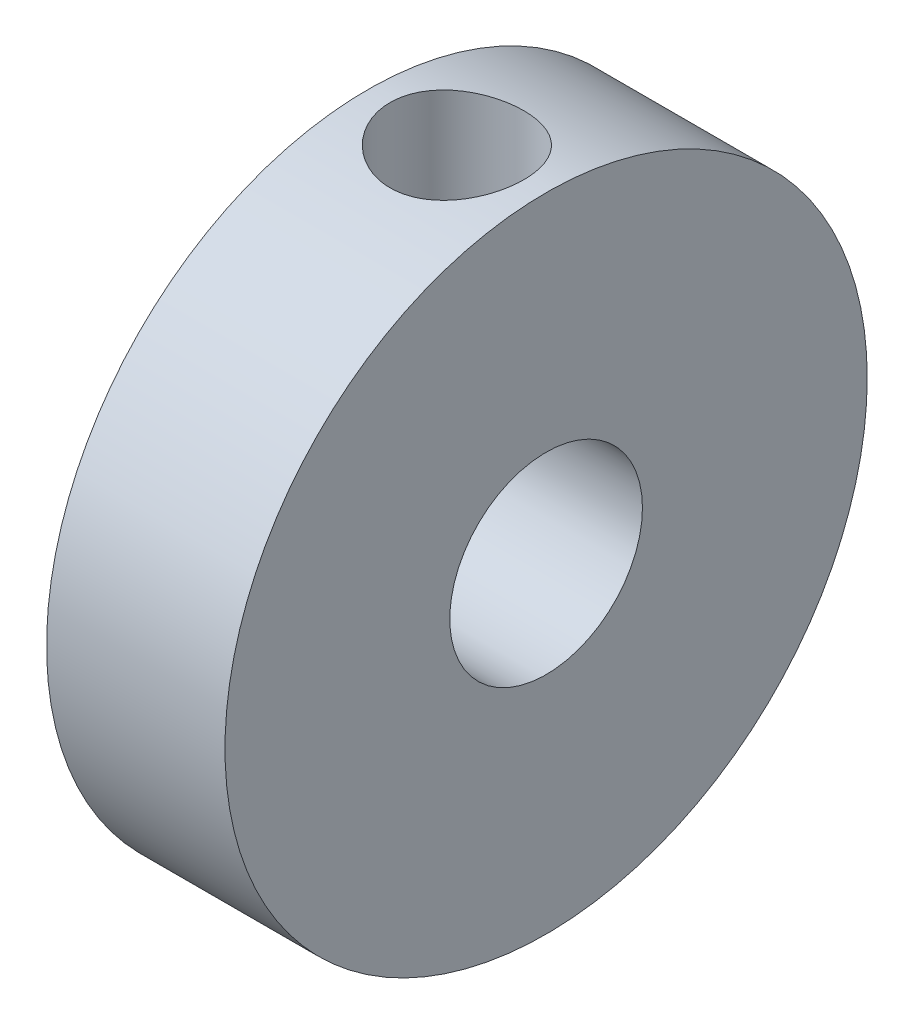
SolidWorks part; units mm, degrees
ref_plane "Front Plane" through (0, 0, 0) normal (0, 0, 1) x (1, 0, 0)
ref_plane "Top Plane" through (0, 0, 0) normal (0, 1, 0) x (1, 0, 0)
ref_plane "Right Plane" through (0, 0, 0) normal (1, 0, 0) x (0, 0, -1)
sketch "Sketch1" plane through (0, 0, 0) normal (1, 0, 0) x (0, 0, -1)
  circle A0 centre (0, 0) radius 3.429
  circle A1 centre (0, 0) radius 11.43
extrude "Boss-Extrude1" add sketch "Sketch1" along normal blind 6.35
sketch "Sketch2" plane through (0, 0, 0) normal (0, 1, 0) x (1, 0, 0)
  line L0 (6.35, 11.43) -> (0, -11.43)
  line L1 (0, 11.43) -> (6.35, 11.43)
  line L2 (0, 11.43) -> (0, -11.43)
  line L3 (0, -11.43) -> (6.35, -11.43)
  line L4 (6.35, 11.43) -> (6.35, -11.43)
  line L5 (0, 11.43) -> (6.35, -11.43)
  circle A0 centre (3.175, 0) radius 2.3813
extrude "Cut-Extrude1" cut sketch "Sketch2" along normal blind 14.986 contours L5 A0 L0 | L0 A0 L5 | L5 A0 L0 | L0 A0 L5
